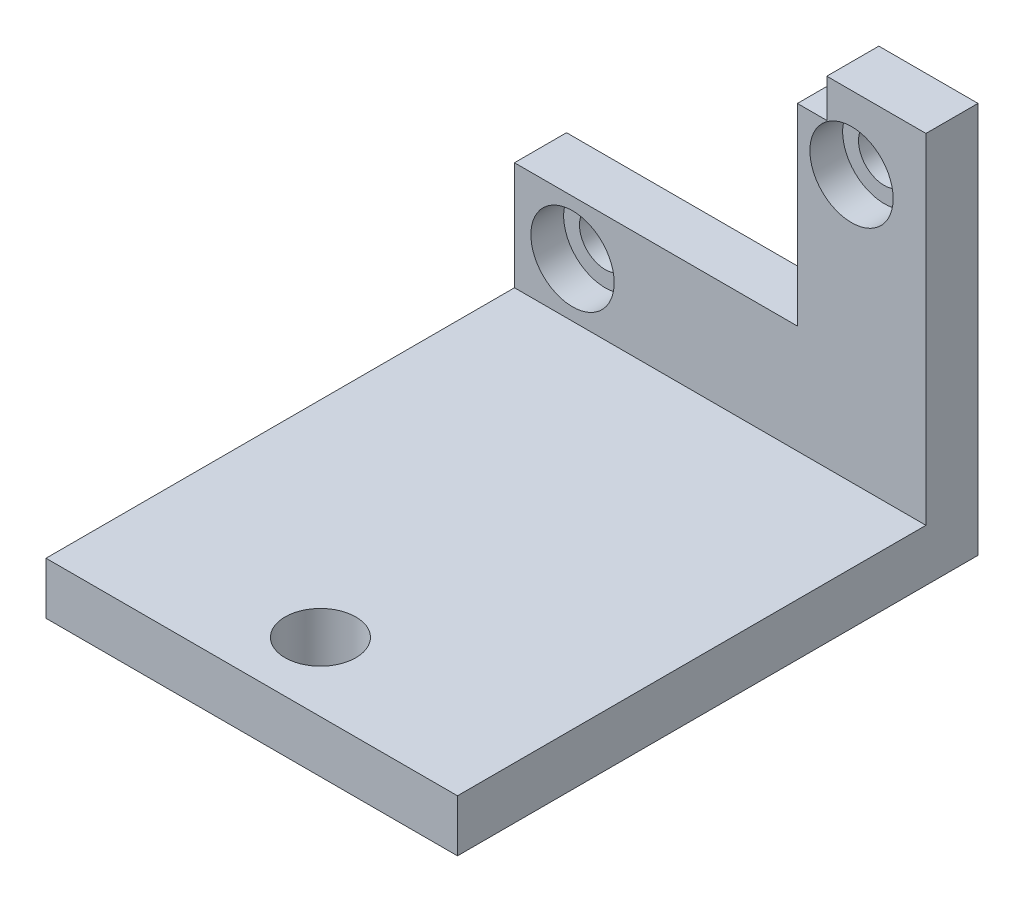
SolidWorks part; units mm, degrees
ref_plane "Front Plane" through (0, 0, 0) normal (0, 0, 1) x (1, 0, 0)
ref_plane "Top Plane" through (0, 0, 0) normal (0, 1, 0) x (1, 0, 0)
ref_plane "Right Plane" through (0, 0, 0) normal (1, 0, 0) x (0, 0, -1)
sketch "Sketch2" plane through (0, 0, 0) normal (0, 0, 1) x (1, 0, 0)
  line L0 (4.3952, 7.8274) -> (4.3952, -1.4384)
  line L1 (4.3952, -1.4384) -> (-11.8608, -1.4384)
  line L2 (-11.8608, -1.4384) -> (-11.8608, -8.0424)
  line L3 (-11.8608, -8.0424) -> (12.2372, -8.0424)
  line L4 (12.2372, -8.0424) -> (12.2372, 12.6586)
  line L5 (12.2372, 12.6586) -> (7.6972, 12.6586)
  line L7 (7.6972, 12.6586) -> (6.1882, 12.6586)
  line L8 (-11.8608, -1.4384) -> (-12.8608, -1.4384)
  line L9 (-11.8608, -1.4384) -> (-11.8608, -8.0424)
  line L10 (-11.8608, -8.0424) -> (-12.8608, -8.0424)
  line L11 (-12.8608, -1.4384) -> (-12.8608, -8.0424)
  line L12 (4.3952, 10.3218) -> (4.3952, 7.8274)
  line L13 (4.3952, 10.3218) -> (6.1882, 10.3218)
  line L14 (6.1882, 10.3218) -> (6.1882, 12.6586)
  circle A0 centre (7.6972, 8.2136) radius 1.5748
  circle A1 centre (-9.3208, -4.7404) radius 1.5748
  point P0 (6.4597, 9.1875)
  dimension "D5" = 4.445
  dimension "D7" = 3.1496
  dimension "D9" = 3.1496
  dimension "D1" = 1
  dimension "D2" = 3.302
  dimension "D3" = 3.302
  dimension "D4" = 24.098
  dimension "D6" = 2.54
  dimension "D8" = 17.018
  dimension "D10" = 14.097
extrude "Boss-Extrude1" add sketch "Sketch2" along normal blind 3.175 contours A0 | L8 L11 L10 L2 | A1
sketch "Sketch3" plane through (0, 0, 0) normal (0, 0, -1) x (-1, 0, 0)
  line L6 (-12.2372, -8.0424) -> (12.8608, -8.0424)
  line L7 (-12.2372, -8.0424) -> (-12.2372, -11.2174)
  line L8 (-12.2372, -11.2174) -> (12.8608, -11.2174)
  line L9 (12.8608, -8.0424) -> (12.8608, -11.2174)
  dimension "D1" = 3.175
extrude "Boss-Extrude3" add sketch "Sketch3" against normal blind 31.75
sketch "Sketch4" plane through (0, -11.2174, 0) normal (0, -1, 0) x (1, 0, 0)
  line L0 (12.2372, 0) -> (-12.8608, 0) construction
  line L1 (-0.3118, 31.75) -> (-0.3118, 3.0754) construction
  line L2 (12.2372, 31.75) -> (-12.8608, 31.75) construction
  circle A0 centre (-0.3118, 27.559) radius 2.159
  dimension "D1" = 4.318
  dimension "D2" = 27.559
extrude "Cut-Extrude1" cut sketch "Sketch4" against normal through all
sketch "Sketch5" plane through (0, 0, 3.175) normal (0, 0, 1) x (1, 0, 0)
  circle A0 centre (7.6972, 8.2136) radius 2.54
  circle A1 centre (-9.3208, -4.7404) radius 2.54
  dimension "D1" = 5.08
  dimension "D2" = 5.08
extrude "Cut-Extrude2" cut sketch "Sketch5" against normal blind 2
